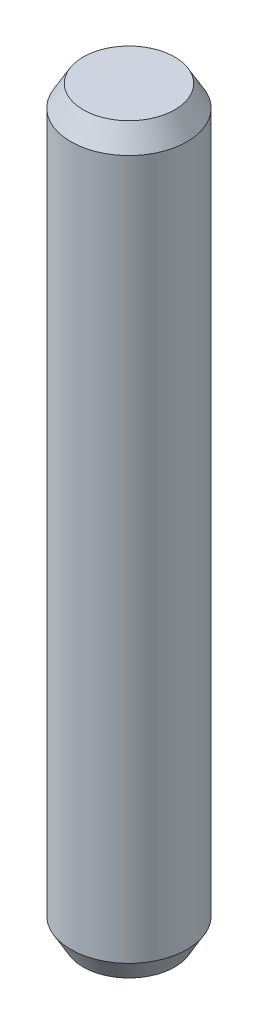
SolidWorks part; units mm, degrees
ref_plane "Front Plane" through (0, 0, 0) normal (0, 0, 1) x (1, 0, 0)
ref_plane "Top Plane" through (0, 0, 0) normal (0, 1, 0) x (1, 0, 0)
ref_plane "Right Plane" through (0, 0, 0) normal (1, 0, 0) x (0, 0, -1)
sketch "Sketch1" plane through (0, 0, 0) normal (0, 1, 0) x (1, 0, 0)
  circle A0 centre (0, 0) radius 4.7
  dimension "D1" = 9.4
extrude "Boss-Extrude1" add sketch "Sketch1" along normal blind 60
chamfer "Chamfer1" distance 1 angle 60 1 edges at (0, 0, 4.7)
ref_plane "Plane1" through (0, 30, 0) normal (0, 1, 0) x (1, 0, 0)
chamfer "Chamfer3" distance 1 angle 60 1 edges at (0, 60, 4.7)
